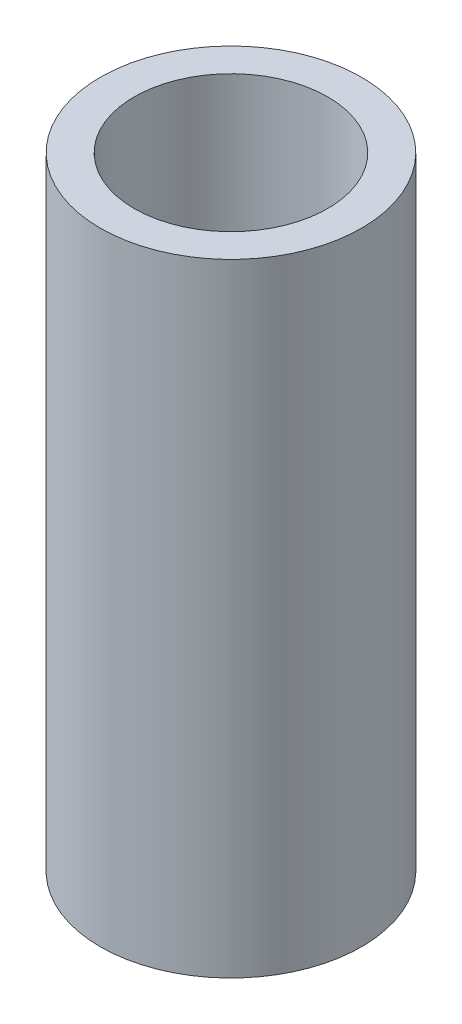
SolidWorks part; units mm, degrees
material "PVC Rigid"
ref_plane "Front Plane" through (0, 0, 0) normal (0, 0, 1) x (1, 0, 0)
ref_plane "Top Plane" through (0, 0, 0) normal (0, 1, 0) x (1, 0, 0)
ref_plane "Right Plane" through (0, 0, 0) normal (1, 0, 0) x (0, 0, -1)
sketch "Sketch1" plane through (0, 0, 0) normal (0, 1, 0) x (1, 0, 0)
  circle A0 centre (0, 0) radius 7.8994
  circle A1 centre (0, 0) radius 10.668
  dimension "D1" = 15.7988
  dimension "D2" = 21.336
extrude "Boss-Extrude1" add sketch "Sketch1" along normal blind 50.8
